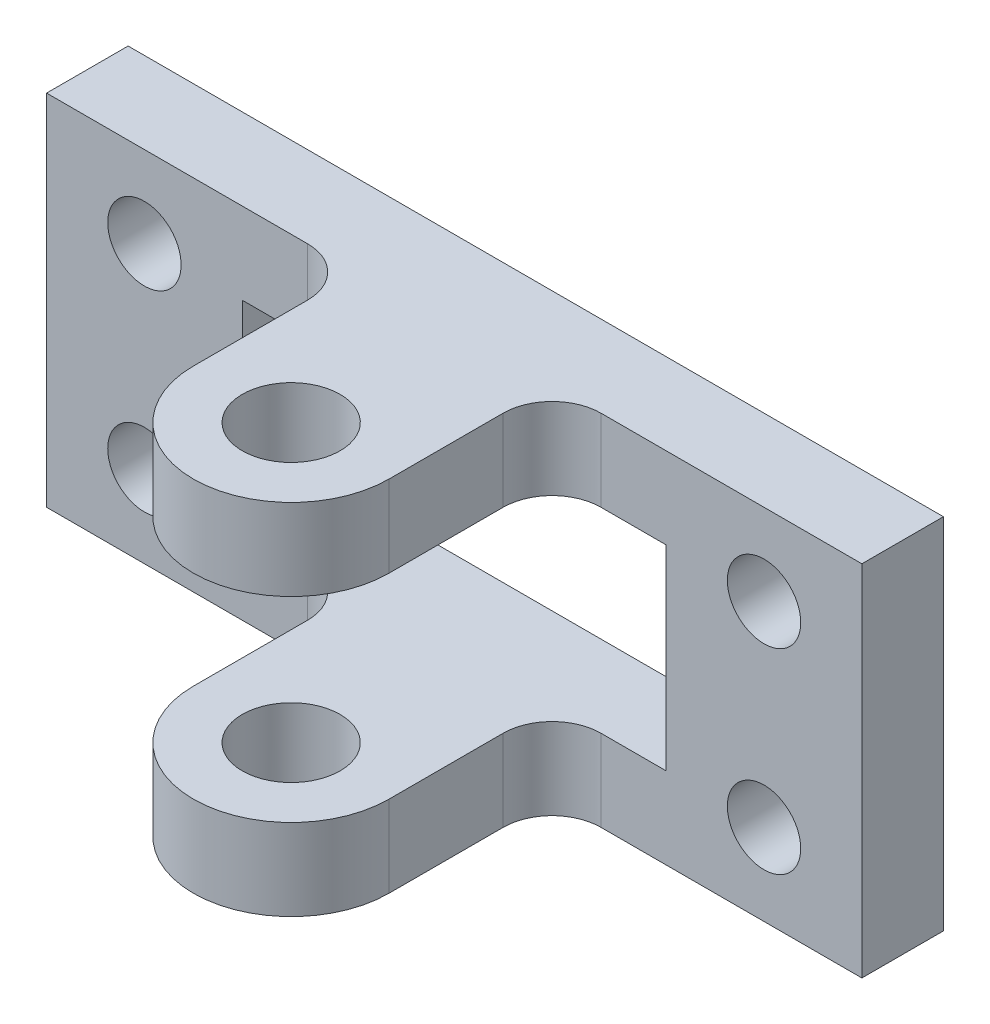
SolidWorks part; units mm, degrees
ref_plane "前视基准面" through (0, 0, 0) normal (0, 0, 1) x (1, 0, 0)
ref_plane "上视基准面" through (0, 0, 0) normal (0, 1, 0) x (1, 0, 0)
ref_plane "右视基准面" through (0, 0, 0) normal (1, 0, 0) x (0, 0, -1)
ref_plane "基准面1" through (0, 0, 15) normal (0, 0, -1) x (-1, 0, 0)
sketch "草图1" plane through (0, 0, 15) normal (0, 0, -1) x (-1, 0, 0)
  line L0 (6, -6) -> (0, -6)
  line L1 (0, -6) -> (0, -11)
  line L2 (0, -11) -> (6, -11)
  line L3 (6, -11) -> (6, -6)
  line L4 (0, -6) -> (0, -11) construction
revolve "旋转1" add sketch "草图1" angle 180 about L4
sketch "草图2" plane through (0, 0, 15) normal (0, 0, -1) x (-1, 0, 0)
  line L0 (6, -6) -> (6, -11)
  line L1 (6, -11) -> (-6, -11)
  line L2 (-6, -11) -> (-6, -6)
  line L3 (-6, -6) -> (6, -6)
extrude "凸台-拉伸1" add sketch "草图2" along normal blind 15
sketch "草图3" plane through (-6, 0, 0) normal (-1, 0, 0) x (0, 0, 1)
  line L0 (5, -6) -> (5, -11)
  line L1 (5, -11) -> (0, -11)
  line L2 (0, -11) -> (0, -6)
  line L3 (0, -6) -> (5, -6)
extrude "凸台-拉伸2" add sketch "草图3" along normal blind 19
sketch "草图4" plane through (6, 0, 0) normal (1, 0, 0) x (0, 0, -1)
  line L0 (0, -6) -> (0, -11)
  line L1 (0, -11) -> (-5, -11)
  line L2 (-5, -11) -> (-5, -6)
  line L3 (-5, -6) -> (0, -6)
extrude "凸台-拉伸3" add sketch "草图4" along normal blind 19
sketch "草图5" plane through (0, -6, 0) normal (0, 1, 0) x (-1, 0, 0)
  line L0 (-25, 5) -> (-13, 5)
  line L1 (-13, 5) -> (-13, 0)
  line L2 (-13, 0) -> (-25, 0)
  line L3 (-25, 0) -> (-25, 5)
extrude "凸台-拉伸4" add sketch "草图5" along normal blind 12
sketch "草图6" plane through (0, -6, 0) normal (0, 1, 0) x (-1, 0, 0)
  line L0 (25, 0) -> (13, 0)
  line L1 (13, 0) -> (13, 5)
  line L2 (13, 5) -> (25, 5)
  line L3 (25, 5) -> (25, 0)
extrude "凸台-拉伸5" add sketch "草图6" along normal blind 12
sketch "草图7" plane through (0, 6, 0) normal (0, 1, 0) x (-1, 0, 0)
  line L0 (25, 5) -> (25, 0)
  line L1 (25, 0) -> (-25, 0)
  line L2 (-25, 0) -> (-25, 5)
  line L3 (-25, 5) -> (-6, 5)
  line L4 (-6, 5) -> (-6, 15)
  line L5 (6, 15) -> (6, 5)
  line L6 (6, 5) -> (25, 5)
  arc A0 (-6, 15) -> (6, 15) centre (0, 15) cw
extrude "凸台-拉伸6" add sketch "草图7" along normal blind 5
hole_wizard "Ø6.0 (6) 直径孔1" positions "草图9" profile "草图8" hole size "Ø6.0" standard "ANSI Metric"
sketch "草图9" plane through (0, 6, 0) normal (0, -1, 0) x (-1, 0, 0)
  point P0 (0, -15)
sketch "草图8" plane through (0, 6, 15) normal (1, 0, 0) x (0, 0, -1)
  line L0 (0, 0) -> (0, 5)
  line L1 (0, 5) -> (3, 5)
  line L2 (3, 5) -> (3, 0)
  line L5 (3, 0) -> (0, 0)
  line L11 (0, -6.35) -> (0, 107.95) construction
  dimension "通孔孔直径" = 6
  dimension "通孔孔深度" = 5
hole_wizard "Ø6.0 (6) 直径孔2" positions "草图13" profile "草图12" hole size "Ø6.0" standard "ANSI Metric"
sketch "草图13" plane through (0, -11, 0) normal (0, -1, 0) x (-1, 0, 0)
  point P0 (0, -15)
sketch "草图12" plane through (0, -11, 15) normal (1, 0, 0) x (0, 0, -1)
  line L0 (0, 0) -> (0, 22)
  line L1 (0, 22) -> (3, 22)
  line L2 (3, 22) -> (3, 0)
  line L5 (3, 0) -> (0, 0)
  line L11 (0, -6.35) -> (0, 107.95) construction
  dimension "通孔孔直径" = 6
  dimension "通孔孔深度" = 22
hole_wizard "Ø4.5 (4.5) 直径孔1" positions "草图15" profile "草图14" hole size "Ø4.5" standard "ANSI Metric" end condition through all
sketch "草图15" plane through (0, 0, 0) normal (0, 0, -1) x (-1, 0, 0)
  point P0 (-19, -6)
  point P1 (19, 6)
  point P2 (19, -6)
  point P3 (-19, 6)
sketch "草图14" plane through (19, -6, 0) normal (1, 0, 0) x (0, 1, 0)
  line L0 (0, 0) -> (0, 21)
  line L1 (0, 21) -> (2.25, 21)
  line L2 (2.25, 21) -> (2.25, 0)
  line L5 (2.25, 0) -> (0, 0)
  line L11 (0, -6.35) -> (0, 107.95) construction
  dimension "通孔孔直径" = 4.5
  dimension "通孔孔深度" = 21
fillet "圆角1" radius 3 4 edges at (-6, 8.5, 5) (6, 8.5, 5) (-6, -8.5, 5) (6, -8.5, 5)
